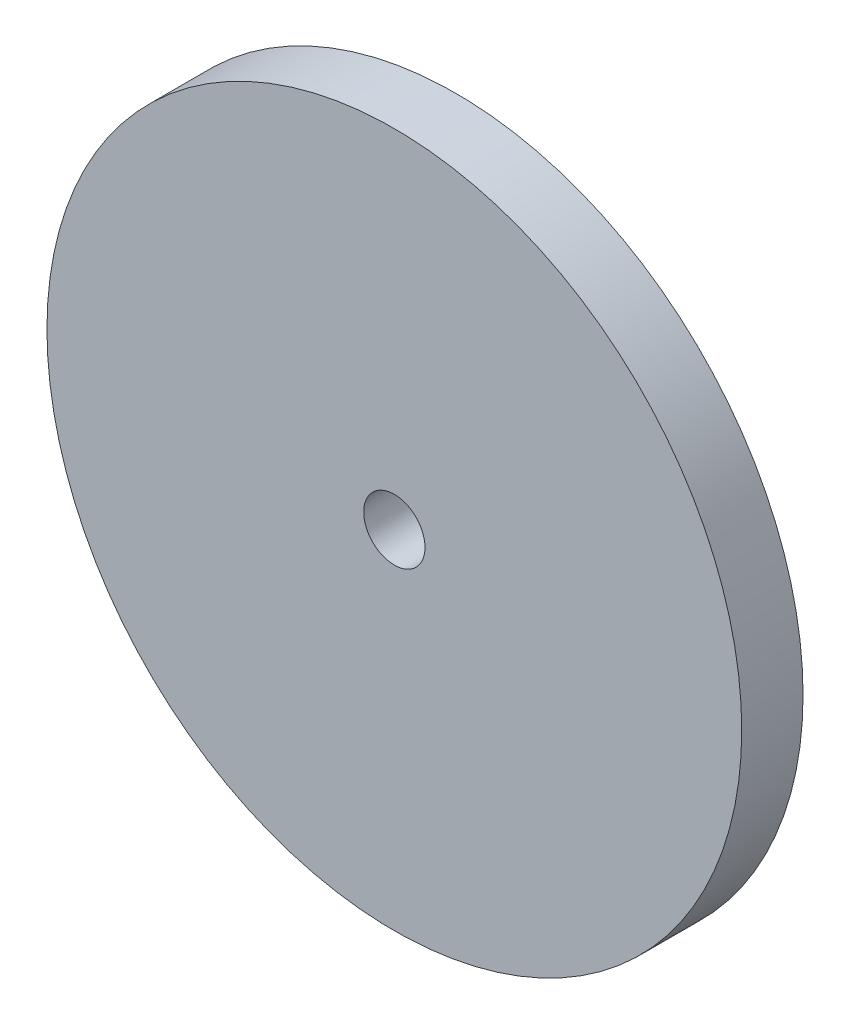
SolidWorks part; units mm, degrees
ref_plane "Front Plane" through (0, 0, 0) normal (0, 0, 1) x (1, 0, 0)
ref_plane "Top Plane" through (0, 0, 0) normal (0, 1, 0) x (1, 0, 0)
ref_plane "Right Plane" through (0, 0, 0) normal (1, 0, 0) x (0, 0, -1)
sketch "Sketch4" plane through (0, 0, 0) normal (0, 0, 1) x (1, 0, 0)
  circle A0 centre (0, 0) radius 17
  dimension "D1" = 34
extrude "Boss-Extrude2" add sketch "Sketch4" along normal blind 3
sketch "Sketch3" plane through (0, 0, 0) normal (0, 0, 1) x (-1, 0, 0)
  circle A2 centre (0, 0) radius 1.5
  dimension "D1" = 3
extrude "Cut-Extrude4" cut sketch "Sketch3" along normal through all
